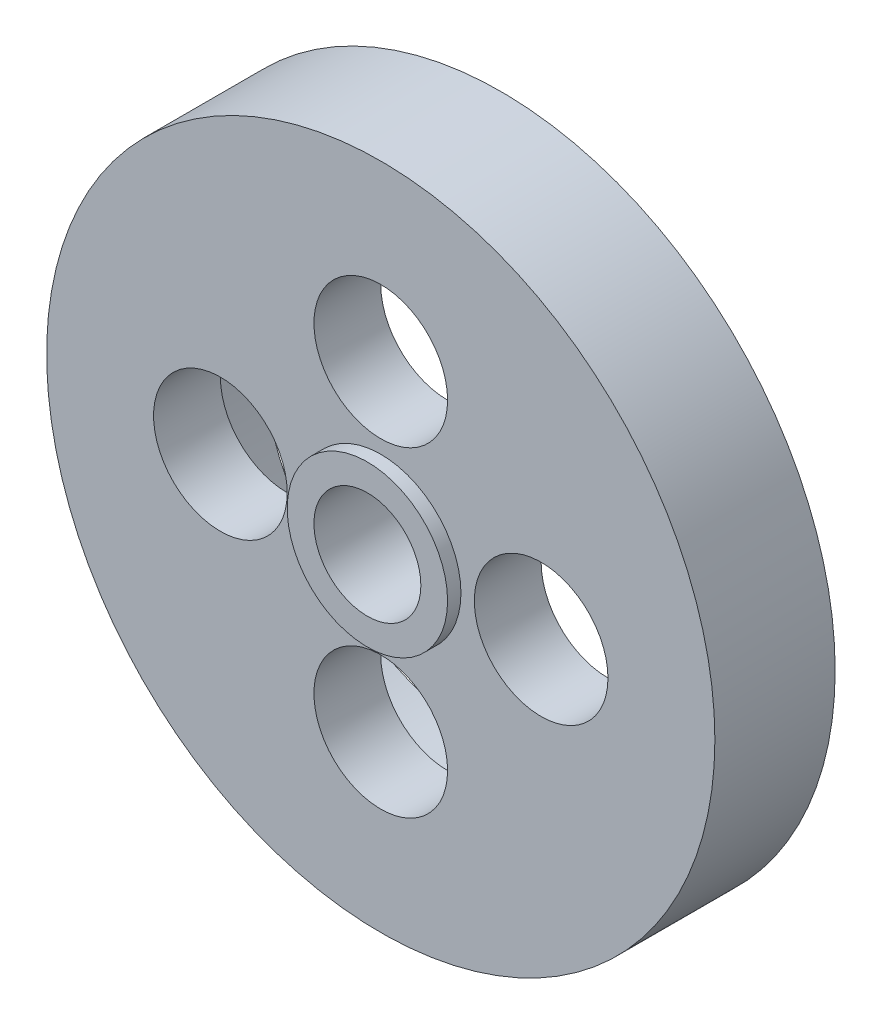
SolidWorks part; units mm, degrees
ref_plane "Front Plane" through (0, 0, 0) normal (0, 0, 1) x (1, 0, 0)
ref_plane "Top Plane" through (0, 0, 0) normal (0, 1, 0) x (1, 0, 0)
ref_plane "Right Plane" through (0, 0, 0) normal (1, 0, 0) x (0, 0, -1)
sketch "Sketch1" plane through (0, 0, 0) normal (0, 0, 1) x (1, 0, 0)
  circle A0 centre (0, 0) radius 25
  dimension "D1" = 50
extrude "Boss-Extrude1" add sketch "Sketch1" along normal blind 9
sketch "Sketch2" plane through (0, 0, 0) normal (0, 0, -1) x (-1, 0, 0)
  circle A0 centre (0, 0) radius 18
  dimension "D1" = 36
extrude "Cut-Extrude1" cut sketch "Sketch2" against normal blind 4
sketch "Sketch3" plane through (0, 0, 9) normal (0, 0, 1) x (1, 0, 0)
  circle A0 centre (0, 0) radius 12 construction
  circle A1 centre (0, 12) radius 5
  circle A2 centre (12, 0) radius 5
  circle A3 centre (0, -12) radius 5
  circle A4 centre (-12, 0) radius 5
  circle A5 centre (0, 0) radius 25 construction
  point P14 (0, 0)
  dimension "D1" = 24
  dimension "D2" = 10
  dimension "D3" = 4
extrude "Cut-Extrude2" cut sketch "Sketch3" against normal through all
sketch "Sketch4" plane through (0, 0, 9) normal (0, 0, 1) x (1, 0, 0)
  circle A0 centre (0, 0) radius 6
  dimension "D1" = 12
extrude "Boss-Extrude2" add sketch "Sketch4" along normal blind 1
sketch "Sketch5" plane through (0, 0, 10) normal (0, 0, 1) x (1, 0, 0)
  circle A0 centre (0, 0) radius 4
  dimension "D1" = 8
extrude "Cut-Extrude3" cut sketch "Sketch5" against normal through all
